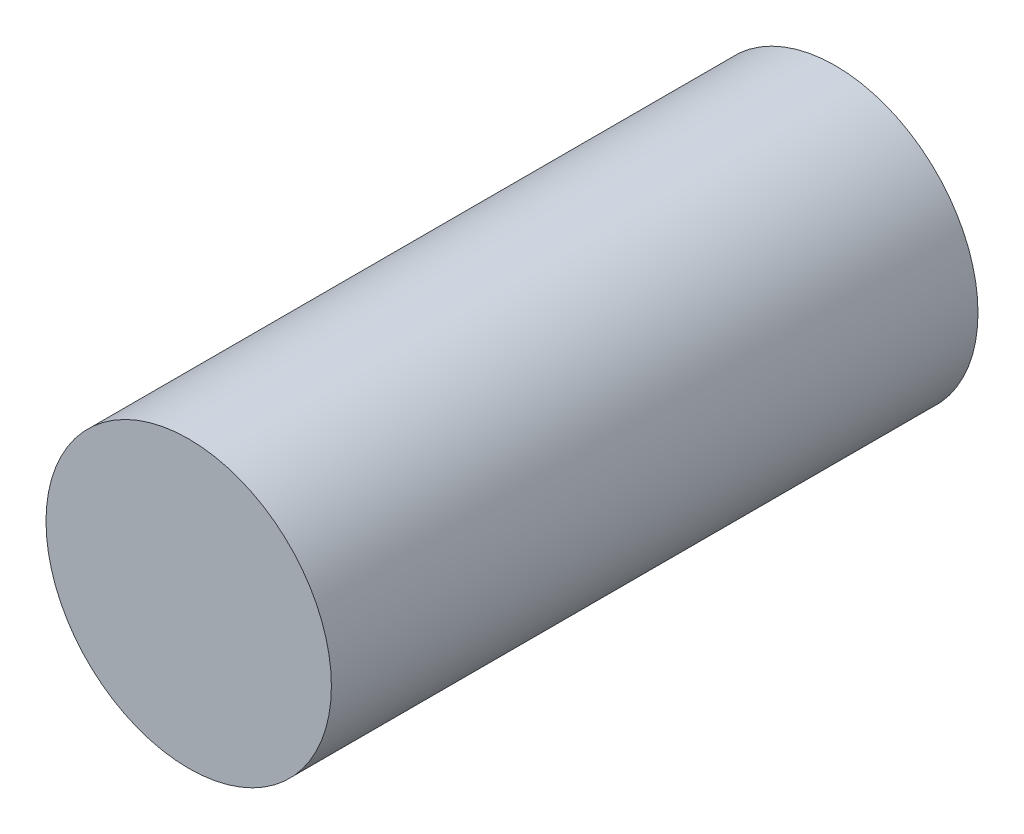
SolidWorks part; units mm, degrees
ref_plane "Front Plane" through (0, 0, 0) normal (0, 0, 1) x (1, 0, 0)
ref_plane "Top Plane" through (0, 0, 0) normal (0, 1, 0) x (1, 0, 0)
ref_plane "Right Plane" through (0, 0, 0) normal (1, 0, 0) x (0, 0, -1)
sketch "Sketch1" plane through (0, 0, 0) normal (0, 0, 1) x (1, 0, 0)
  circle A0 centre (0, 0) radius 3.2
  dimension "D1" = 6.4
extrude "Boss-Extrude1" add sketch "Sketch1" along normal blind 14.5
scale "缩放比例1" scale about centroid uniform scaling yes scale factor 2
